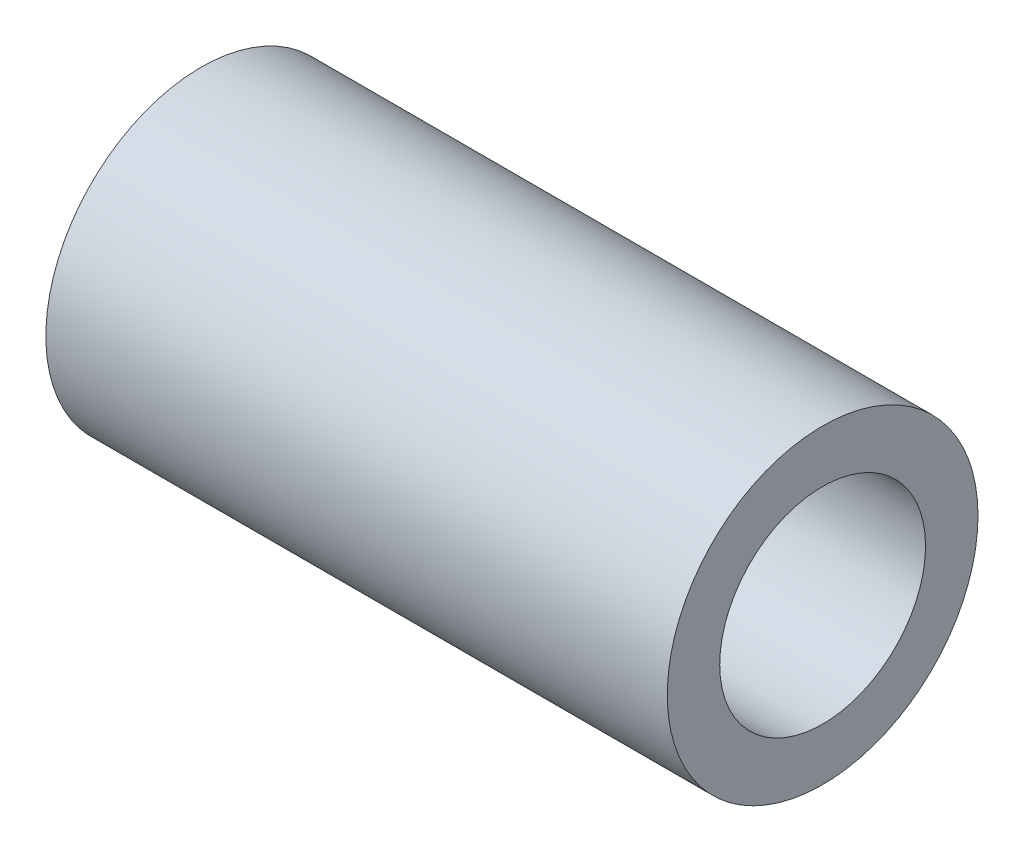
SolidWorks part; units mm, degrees
material "ABS"
ref_plane "前视基准面" through (0, 0, 0) normal (0, 0, 1) x (1, 0, 0)
ref_plane "上视基准面" through (0, 0, 0) normal (0, 1, 0) x (1, 0, 0)
ref_plane "右视基准面" through (0, 0, 0) normal (1, 0, 0) x (0, 0, -1)
other "Configuration Table"
sketch "草图1" plane through (0, 0, 0) normal (1, 0, 0) x (0, 0, -1)
  circle A0 centre (0, 0) radius 2.65
  circle A1 centre (0, 0) radius 4
  dimension "D1" = 5.3
  dimension "D2" = 8
extrude "凸台-拉伸1" add sketch "草图1" along normal blind 16
